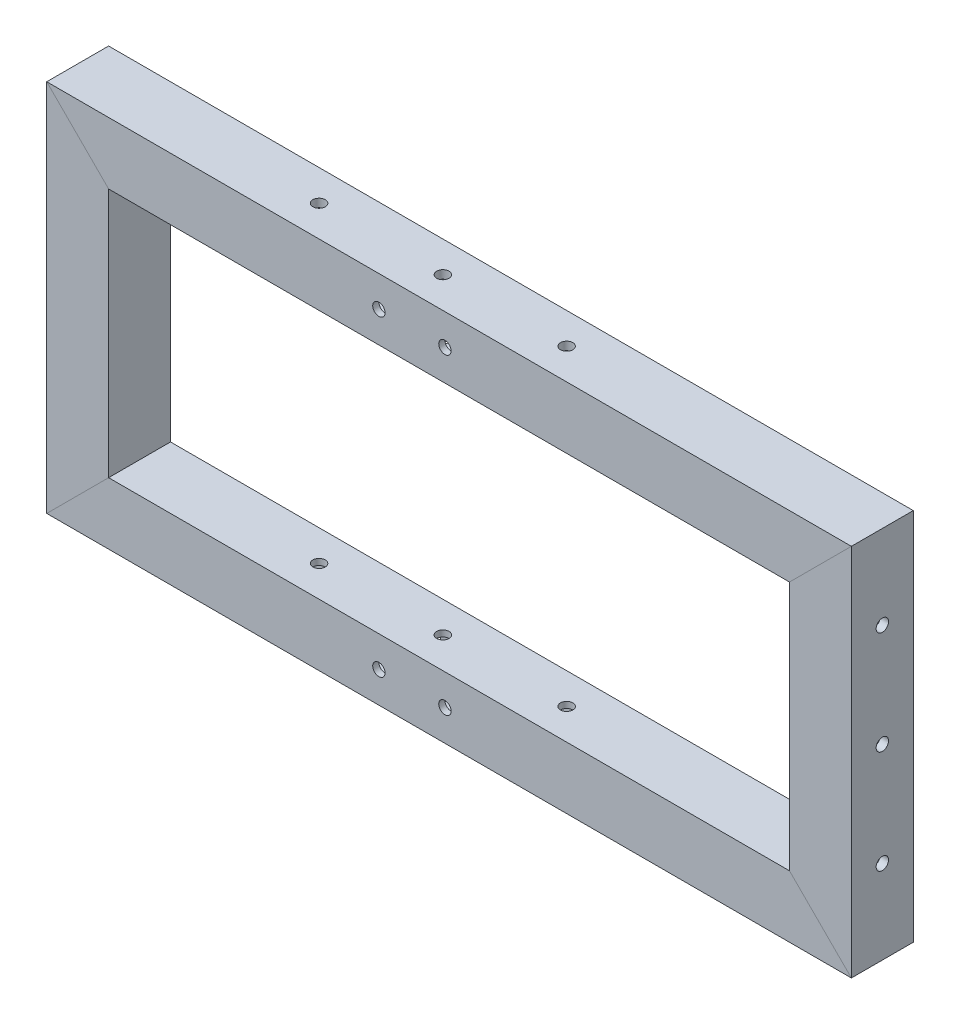
SolidWorks part; units mm, degrees
material "6061 合金"
ref_plane "前视基准面" through (0, 0, 0) normal (0, 0, 1) x (1, 0, 0)
ref_plane "上视基准面" through (0, 0, 0) normal (0, 1, 0) x (1, 0, 0)
ref_plane "右视基准面" through (0, 0, 0) normal (1, 0, 0) x (0, 0, -1)
sketch3d "3D草图1"
  line L1 (0, 0, 0) -> (180, 0, 0)
  line L2 (0, 0, 0) -> (0, 75.6, 0)
  line L3 (0, 75.6, 0) -> (180, 75.6, 0)
  line L4 (180, 0, 0) -> (180, 75.6, 0)
  dimension "D1" = 180
  dimension "D2" = 75.6
other "方形管 15 ×15× 1.5(1)"
ref_plane "基准面1" through (0, 0, 0) normal (0, 1, 0) x (1, 0, 0)
sketch "Sketch1" plane through (0, 0, 0) normal (0, 1, 0) x (1, 0, 0)
  line L0 (-4, -6) -> (4, -6)
  line L1 (-5.5, -3.5) -> (-5.5, 3.5)
  line L2 (3.5, 6) -> (-3.5, 6)
  line L3 (6, 3.5) -> (6, -3.5)
  line L4 (-6, -7.5) -> (6, -7.5)
  line L5 (-7.5, -6) -> (-7.5, 6)
  line L6 (6, 7.5) -> (-6, 7.5)
  line L7 (7.5, 6) -> (7.5, -6)
  line L8 (-5.5, 3.5) -> (-5.5, 6)
  line L9 (-5.5, 6) -> (-3.5, 6)
  line L10 (-7.5, 6) -> (-7.5, 7.5)
  line L11 (-7.5, 7.5) -> (-6, 7.5)
  line L12 (6, 7.5) -> (7.5, 7.5)
  line L13 (7.5, 7.5) -> (7.5, 6)
  line L14 (3.5, 6) -> (6, 6)
  line L15 (6, 6) -> (6, 3.5)
  line L16 (4, -6) -> (6, -6)
  line L17 (6, -6) -> (6, -3.5)
  line L18 (7.5, -6) -> (7.5, -7.5)
  line L19 (7.5, -7.5) -> (6, -7.5)
  line L20 (-5.5, -3.5) -> (-5.5, -6)
  line L21 (-5.5, -6) -> (-4, -6)
  line L22 (-7.5, -6) -> (-7.5, -7.5)
  line L23 (-7.5, -7.5) -> (-6, -7.5)
  line L24 (0, 7.5) -> (0, -7.5) construction
  line L25 (-7.5, 0) -> (7.5, 0) construction
  point P0 (-7.5, 0)
  point P1 (7.5, 0)
  point P2 (0, 7.5)
  point P3 (0, -7.5)
  point P4 (0, 0)
  point P5 (-7.5, -7.5)
  point P6 (7.5, -7.5)
  point P7 (7.5, 7.5)
  point P8 (-7.5, 7.5)
  point P38 (6, 0)
  point P39 (-5.5, 0)
  point P40 (0, 6)
  point P41 (0, -6)
  point P42 (0, 0)
  dimension "D1" = 1.5
  dimension "D2" = 1.5
  dimension "D3" = 1.5
  dimension "D4" = 1.5
  dimension "D5" = 1.5
  dimension "D6" = 12
  dimension "D7" = 1.5
  dimension "D8" = 1.5
  dimension "Thickness" = 2
  dimension "D9" = 1.5
  dimension "D10" = 1.5
sketch "草图3" plane through (0, -7.5, 0) normal (0, -1, 0) x (1, 0, 0)
  line L0 (81, 7.5) -> (81, -7.5) construction
  line L1 (-7.5, 7.5) -> (187.5, 7.5) construction
  line L2 (-7.5, -7.5) -> (187.5, -7.5) construction
  line L3 (-7.5, 7.5) -> (-7.5, -7.5) construction
  line L4 (81, 0) -> (51, 0) construction
  circle A0 centre (81, 0) radius 1.5
  circle A1 centre (51, 0) radius 1.5
  circle A2 centre (111, 0) radius 1.5
  dimension "D1" = 88.5
  dimension "D2" = 3
  dimension "D3" = 30
extrude "切除-拉伸1" cut sketch "草图3" against normal through all
sketch "草图4" plane through (0, 0, 7.5) normal (0, 0, 1) x (1, 0, 0)
  line L1 (7.5, 7.5) -> (172.5, 7.5) construction
  line L2 (172.5, 37.8) -> (7.5, 37.8) construction
  line L3 (172.5, 7.5) -> (172.5, 68.1) construction
  line L4 (7.5, 68.1) -> (7.5, 7.5) construction
  line L5 (-7.5, 83.1) -> (-7.5, -7.5) construction
  circle A0 centre (89, 0) radius 1.5
  circle A1 centre (73, 0) radius 1.5
  circle A2 centre (73, 75.6) radius 1.5
  circle A3 centre (89, 75.6) radius 1.5
  dimension "D1" = 16
  dimension "D3" = 3
  dimension "D2" = 80.5
  dimension "D4" = 7.5
extrude "切除-拉伸2" cut sketch "草图4" against normal through all
sketch "草图6" plane through (187.5, 0, 0) normal (1, 0, 0) x (0, 0, -1)
  line L0 (0, -7.5) -> (0, 83.1) construction
  line L1 (-7.5, -7.5) -> (7.5, -7.5) construction
  line L2 (7.5, 83.1) -> (-7.5, 83.1) construction
  line L3 (0, 37.8) -> (-7.5, 37.8) construction
  line L4 (-7.5, -7.5) -> (-7.5, 83.1) construction
  circle A0 centre (0, 37.8) radius 1.5
  circle A1 centre (0, 12.8) radius 1.5
  circle A2 centre (0, 62.8) radius 1.5
  dimension "D1" = 3
  dimension "D2" = 25
extrude "切除-拉伸3" cut sketch "草图6" against normal blind 15
sketch "草图7" plane through (0, 0, 7.5) normal (0, 0, 1) x (1, 0, 0)
  line L0 (-7.5, 83.1) -> (7.5, 68.1) construction
  line L1 (-15, 60.6) -> (15, 60.6)
  line L2 (-15, 60.6) -> (-15, 90.6)
  line L3 (-15, 90.6) -> (15, 90.6)
  line L4 (15, 60.6) -> (15, 90.6)
  line L5 (-15, 60.6) -> (15, 90.6) construction
  line L6 (-15, 90.6) -> (15, 60.6) construction
  line L7 (7.5, 37.8) -> (172.5, 37.8) construction
  line L8 (7.5, 68.1) -> (7.5, 7.5) construction
  line L9 (172.5, 7.5) -> (172.5, 68.1) construction
  line L10 (90, 37.8) -> (90, 68.1) construction
  line L11 (172.5, 68.1) -> (7.5, 68.1) construction
  line L12 (195, 90.6) -> (165, 90.6)
  line L13 (165, 60.6) -> (165, 90.6)
  line L14 (195, 60.6) -> (165, 60.6)
  line L15 (195, 60.6) -> (195, 90.6)
  line L16 (-15, -15) -> (15, -15)
  line L17 (15, 15) -> (15, -15)
  line L18 (-15, 15) -> (15, 15)
  line L19 (-15, 15) -> (-15, -15)
  line L20 (195, 15) -> (195, -15)
  line L21 (195, 15) -> (165, 15)
  line L22 (165, 15) -> (165, -15)
  line L23 (195, -15) -> (165, -15)
  line L24 (-7.5, -7.5) -> (187.5, -7.5) construction
  line L25 (35, -9) -> (145, -9)
  line L26 (35, -9) -> (35, -7.5)
  line L27 (35, -7.5) -> (145, -7.5)
  line L28 (145, -9) -> (145, -7.5)
  line L29 (35, 83.1) -> (145, 83.1)
  line L30 (145, 84.6) -> (145, 83.1)
  line L31 (35, 84.6) -> (145, 84.6)
  line L32 (35, 84.6) -> (35, 83.1)
  line L33 (35, 7.5) -> (145, 7.5)
  line L34 (35, 66.6) -> (145, 66.6)
  line L35 (35, 66.6) -> (35, 68.1)
  line L36 (35, 68.1) -> (145, 68.1)
  line L37 (145, 66.6) -> (145, 68.1)
  line L38 (145, 9) -> (145, 7.5)
  line L39 (35, 9) -> (145, 9)
  line L40 (35, 9) -> (35, 7.5)
  line L41 (-7.5, 83.1) -> (-7.5, -7.5) construction
  line L42 (-9, 23) -> (-7.5, 23)
  line L43 (-9, 23) -> (-9, 52.6)
  line L44 (-9, 52.6) -> (-7.5, 52.6)
  line L45 (-7.5, 23) -> (-7.5, 52.6)
  line L46 (189, 52.6) -> (187.5, 52.6)
  line L47 (9, 23) -> (7.5, 23)
  line L48 (9, 23) -> (9, 52.6)
  line L49 (9, 52.6) -> (7.5, 52.6)
  line L50 (7.5, 23) -> (7.5, 52.6)
  line L51 (187.5, 23) -> (187.5, 52.6)
  line L52 (189, 23) -> (187.5, 23)
  line L53 (189, 23) -> (189, 52.6)
  line L54 (171, 52.6) -> (172.5, 52.6)
  line L55 (172.5, 23) -> (172.5, 52.6)
  line L56 (171, 23) -> (172.5, 23)
  line L57 (171, 23) -> (171, 52.6)
  line L59 (-30, -30) -> (210, -30)
  line L60 (-30, -30) -> (-30, 105.6)
  line L61 (-30, 105.6) -> (210, 105.6)
  line L62 (210, -30) -> (210, 105.6)
  line L63 (-30, -30) -> (210, 105.6) construction
  line L64 (-30, 105.6) -> (210, -30) construction
  point P0 (0, 75.6)
  dimension "D1" = 30
  dimension "D2" = 1.5
  dimension "D3" = 20
  dimension "D4" = 20
  dimension "D5" = 1.5
  dimension "D6" = 8
  dimension "D7" = 8
  dimension "D8" = 8
  dimension "D9" = 8
  dimension "D10" = 1.5
  dimension "D11" = 1.5
  dimension "D12" = 15
  dimension "D13" = 15
extrude "凸台-拉伸1" [suppressed] add sketch "草图7" along normal blind 1 separate body
sketch "草图8" [suppressed] plane through (0, 0, 8.5) normal (0, 0, 1) x (1, 0, 0)
  line L0 (0, 0) -> (180, 0) construction
  line L1 (187.5, -7.5) -> (172.5, 7.5) construction
  line L2 (180, 0) -> (180, 75.6) construction
  line L3 (187.5, 83.1) -> (172.5, 68.1) construction
  line L4 (180, 75.6) -> (0, 75.6) construction
  line L5 (7.5, 68.1) -> (-7.5, 83.1) construction
  line L6 (0, 75.6) -> (0, 0) construction
  line L7 (-7.5, 37.8) -> (187.5, 37.8) construction
  line L8 (-7.5, 23) -> (-7.5, 52.6) construction
  line L9 (187.5, 52.6) -> (187.5, 23) construction
  line L10 (15, -15) -> (15, 15) construction
  line L11 (90, 0) -> (90, 75.6) construction
  circle A0 centre (0, 17.8) radius 1.5
  circle A1 centre (0, 57.8) radius 1.5
  circle A2 centre (20, 0) radius 1.5
  circle A3 centre (180, 17.8) radius 1.5
  circle A4 centre (160, 0) radius 1.5
  circle A5 centre (180, 57.8) radius 1.5
  circle A6 centre (160, 75.6) radius 1.5
  circle A7 centre (20, 75.6) radius 1.5
  circle A8 centre (89, 0) radius 1.5
  circle A9 centre (73, 0) radius 1.5
  circle A10 centre (73, 75.6) radius 1.5
  circle A11 centre (89, 75.6) radius 1.5
  point P41 (0, 0)
  dimension "D1" = 20
  dimension "D2" = 3
  dimension "D3" = 5
  dimension "D4" = 3
  dimension "D5" = 16
  dimension "D7" = 3
  dimension "D6" = 71
extrude "切除-拉伸4" [suppressed] cut sketch "草图8" against normal blind 1
